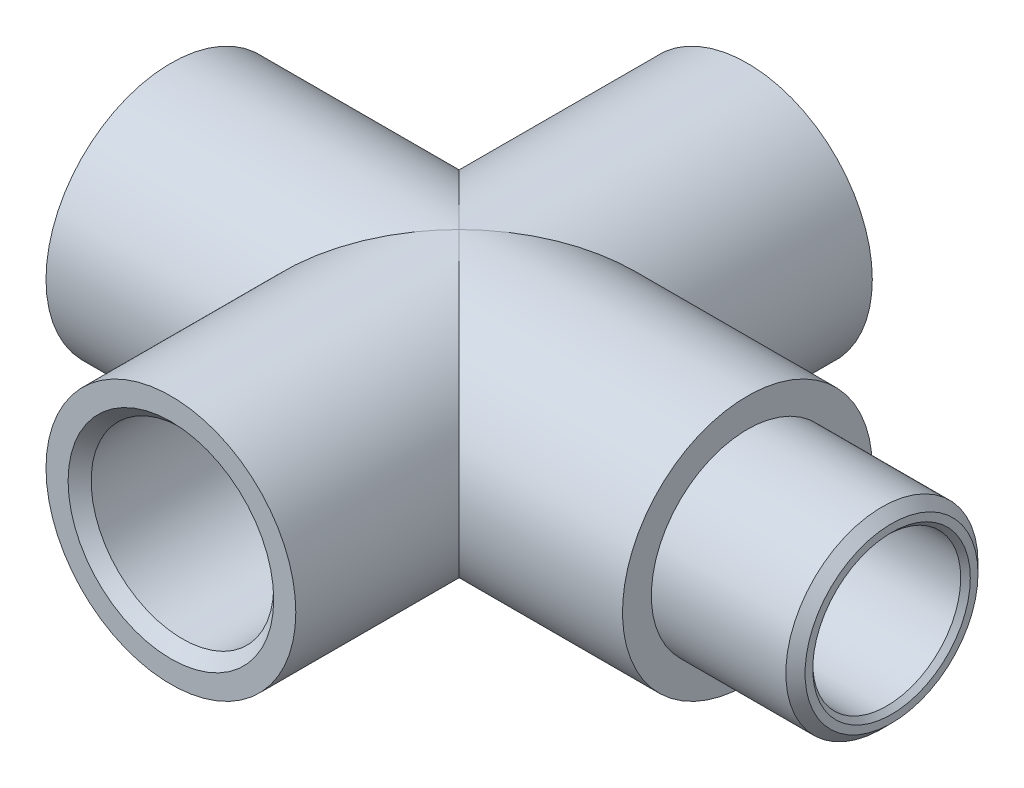
SolidWorks part; units mm, degrees
ref_plane "前视基准面" through (0, 0, 0) normal (0, 0, 1) x (1, 0, 0)
ref_plane "上视基准面" through (0, 0, 0) normal (0, 1, 0) x (1, 0, 0)
ref_plane "右视基准面" through (0, 0, 0) normal (1, 0, 0) x (0, 0, -1)
sketch "草图1" plane through (0, 0, 0) normal (0, 0, 1) x (1, 0, 0)
  circle A0 centre (0, 0) radius 13
  dimension "D1" = 26
extrude "拉伸1" add sketch "草图1" along normal mid plane 60
sketch "草图2" plane through (0, 0, 0) normal (1, 0, 0) x (0, 0, -1)
  circle A0 centre (0, 0) radius 13
  dimension "D1" = 26
extrude "拉伸2" add sketch "草图2" along normal mid plane 90
sketch "草图3" plane through (45, 0, 0) normal (1, 0, 0) x (0, 0, -1)
  circle A0 centre (0, 0) radius 10
  circle A1 centre (0, 0) radius 13 construction
  circle A2 centre (0, 0) radius 13
  dimension "D1" = 20
extrude "切除-拉伸1" cut sketch "草图3" against normal blind 15
sketch "草图4" plane through (0, 0, 30) normal (0, 0, 1) x (1, 0, 0)
  circle A0 centre (0, 0) radius 9.5
  dimension "D1" = 19
extrude "切除-拉伸2" cut sketch "草图4" against normal blind 90
sketch "草图5" plane through (45, 0, 0) normal (1, 0, 0) x (0, 0, -1)
  circle A0 centre (0, 0) radius 7.7
  dimension "D1" = 15.4
extrude "切除-拉伸3" cut sketch "草图5" against normal up to next
sketch "草图6" plane through (-45, 0, 0) normal (-1, 0, 0) x (0, 0, 1)
  circle A0 centre (0, 0) radius 9.5
  dimension "D1" = 19
extrude "切除-拉伸4" cut sketch "草图6" against normal up to next
sketch "草图7" plane through (-45, 0, 0) normal (-1, 0, 0) x (0, 0, 1)
  circle A0 centre (0, 0) radius 13
extrude "切除-拉伸5" cut sketch "草图7" against normal blind 15
chamfer "倒角1" distance 1.2 angle 45 3 edges at (-30, 0, 9.5) (9.5, 0, -30) (9.5, 0, 30)
chamfer "倒角2" distance 1 angle 45 1 edges at (45, 0, -10)
chamfer "倒角3" distance 0.5 angle 45 1 edges at (45, 0, -7.7)
